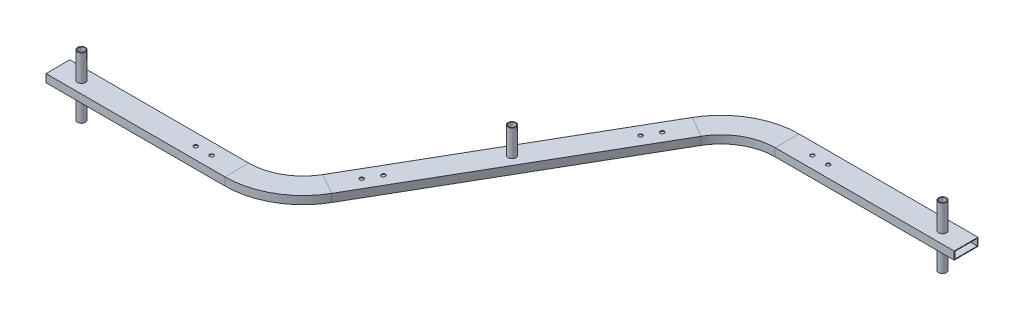
SolidWorks part; units mm, degrees
ref_plane "前视基准面" through (0, 0, 0) normal (0, 0, 1) x (1, 0, 0)
ref_plane "上视基准面" through (0, 0, 0) normal (0, 1, 0) x (1, 0, 0)
ref_plane "右视基准面" through (0, 0, 0) normal (1, 0, 0) x (0, 0, -1)
sketch "草图1" plane through (0, 0, 0) normal (0, 1, 0) x (1, 0, 0)
  line L0 (-2293.0127, -1133.3459) -> (-943.0127, -1133.3459)
  line L1 (-510, -883.3459) -> (510, 883.3459)
  line L2 (943.0127, 1133.3459) -> (2293.0127, 1133.3459)
  arc A0 (510, 883.3459) -> (943.0127, 1133.3459) centre (943.0127, 633.3459) cw
  arc A1 (-943.0127, -1133.3459) -> (-510, -883.3459) centre (-943.0127, -633.3459) ccw
  point P3 (0, 0)
  dimension "D2" = 500
  dimension "D1" = 60
  dimension "D3" = 1350
  dimension "D4" = 2040
ref_plane "基准面1" through (-2293.0127, 0, 1133.3459) normal (1, 0, 0) x (0, 0, -1)
sketch "草图2" plane through (-2293.0127, 0, 1133.3459) normal (1, 0, 0) x (0, 0, -1)
  line L0 (250, 0) -> (0, 0) construction
  line L1 (-90, 30) -> (90, 30)
  line L2 (-90, 30) -> (-90, -30)
  line L3 (-90, -30) -> (90, -30)
  line L4 (90, 30) -> (90, -30)
  line L5 (0, -30) -> (0, 30) construction
  line L6 (-90, 0) -> (90, 0) construction
  line L7 (-85, 25) -> (85, 25)
  line L8 (85, 25) -> (85, -25)
  line L9 (-85, -25) -> (85, -25)
  line L10 (-85, 25) -> (-85, -25)
  point P0 (0, 0)
  dimension "D1" = 180
  dimension "D2" = 60
  dimension "D3" = 5
sweep "扫描1" add profiles "草图2" path "草图1"
sketch "草图3" plane through (0, 30, 0) normal (0, 1, 0) x (1, 0, 0)
  line L0 (-943.0127, -1133.3459) -> (-1133.0127, -1133.3459) construction
  line L1 (-943.0127, -1043.3459) -> (-943.0127, -1223.3459) construction
  line L2 (-1133.0127, -1133.3459) -> (-1253.0127, -1133.3459) construction
  line L3 (-510, -883.3459) -> (-415, -718.8011) construction
  line L4 (-587.9423, -838.3459) -> (-432.0577, -928.3459) construction
  line L5 (-415, -718.8011) -> (-355, -614.878) construction
  line L6 (943.0127, 1133.3459) -> (1133.0127, 1133.3459) construction
  line L7 (1133.0127, 1133.3459) -> (1253.0127, 1133.3459) construction
  line L8 (510, 883.3459) -> (415, 718.8011) construction
  line L9 (415, 718.8011) -> (355, 614.878) construction
  line L10 (432.0577, 928.3459) -> (587.9423, 838.3459) construction
  circle A0 centre (-1253.0127, -1133.3459) radius 15
  circle A1 centre (-1133.0127, -1133.3459) radius 15
  circle A2 centre (-415, -718.8011) radius 15
  circle A3 centre (-355, -614.878) radius 15
  circle A4 centre (1253.0127, 1133.3459) radius 15
  circle A5 centre (1133.0127, 1133.3459) radius 15
  circle A6 centre (415, 718.8011) radius 15
  circle A7 centre (355, 614.878) radius 15
  point P27 (0, 0)
  point P32 (510, 883.3459)
  dimension "D1" = 30
  dimension "D2" = 120
  dimension "D3" = 190
  dimension "D4" = 2
extrude "切除-拉伸1" cut sketch "草图3" against normal through all
sketch "草图4" plane through (0, 30, 0) normal (0, 1, 0) x (1, 0, 0)
  line L0 (2115.5441, 1133.3459) -> (0, 0) construction
  line L1 (0, 0) -> (-2115.5441, -1133.3459) construction
  line L2 (-2293.0127, -1133.3459) -> (-2115.5441, -1133.3459) construction
  line L3 (-2293.0127, -1043.3459) -> (-2293.0127, -1223.3459) construction
  circle A0 centre (0, 0) radius 30
  circle A1 centre (0, 0) radius 25
  circle A2 centre (-2115.5441, -1133.3459) radius 30
  circle A3 centre (-2115.5441, -1133.3459) radius 25
  circle A4 centre (2115.5441, 1133.3459) radius 30
  circle A5 centre (2115.5441, 1133.3459) radius 25
  dimension "D1" = 60
  dimension "D2" = 50
  dimension "D3" = 2400
extrude "凸台-拉伸2" add sketch "草图4" along normal blind 200
sketch "草图5" plane through (0, -30, 0) normal (0, -1, 0) x (1, 0, 0)
  line L0 (2115.5441, -1133.3459) -> (0, 0) construction
  line L1 (0, 0) -> (-2115.5441, 1133.3459) construction
  line L2 (-2293.0127, 1133.3459) -> (-2115.5441, 1133.3459) construction
  line L3 (-2293.0127, 1223.3459) -> (-2293.0127, 1043.3459) construction
  circle A0 centre (-2115.5441, 1133.3459) radius 30
  circle A1 centre (-2115.5441, 1133.3459) radius 25
  circle A2 centre (2115.5441, -1133.3459) radius 30
  circle A3 centre (2115.5441, -1133.3459) radius 25
  dimension "D1" = 60
  dimension "D2" = 50
  dimension "D3" = 2400
extrude "凸台-拉伸3" add sketch "草图5" along normal blind 200
